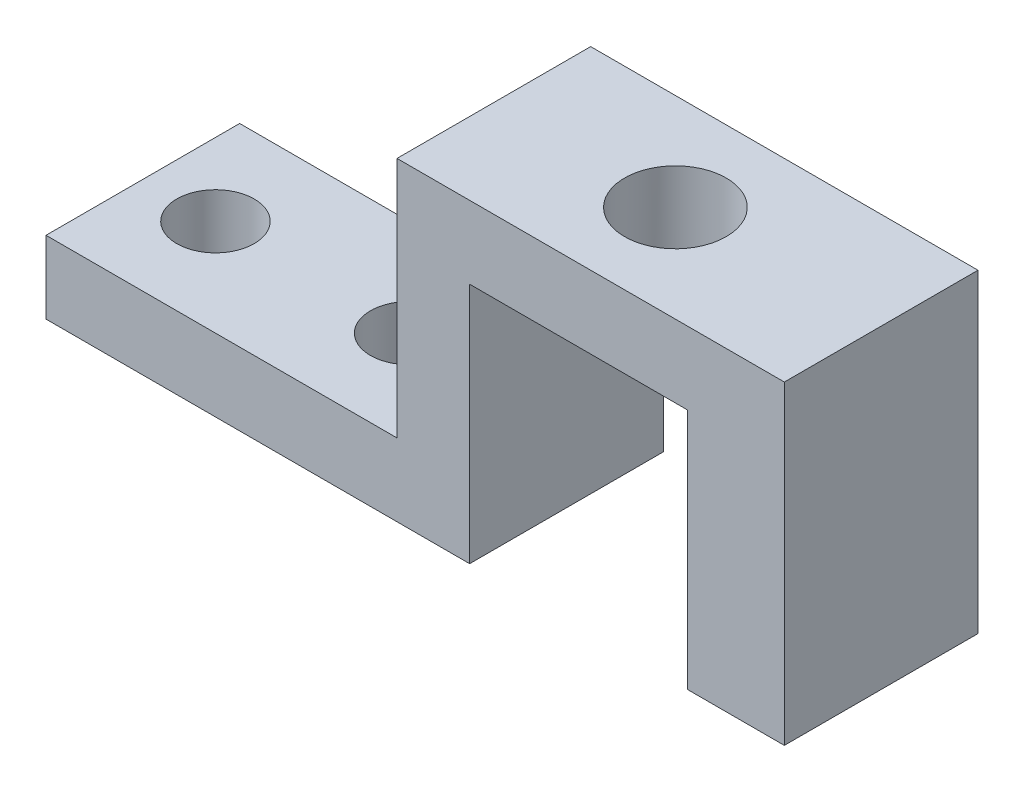
SolidWorks part; units mm, degrees
ref_plane "前视基准面" through (0, 0, 0) normal (0, 0, 1) x (1, 0, 0)
ref_plane "上视基准面" through (0, 0, 0) normal (0, 1, 0) x (1, 0, 0)
ref_plane "右视基准面" through (0, 0, 0) normal (1, 0, 0) x (0, 0, -1)
sketch "草图1" plane through (0, 0, 0) normal (0, 0, 1) x (1, 0, 0)
  line L0 (0, 0) -> (0, 3)
  line L1 (0, 3) -> (14.5, 3)
  line L2 (14.5, 3) -> (14.5, 13)
  line L3 (14.5, 13) -> (30.5, 13)
  line L4 (30.5, 13) -> (30.5, 0)
  line L7 (30.5, 0) -> (26.5, 0)
  line L8 (26.5, 0) -> (26.5, 10)
  line L9 (26.5, 10) -> (17.5, 10)
  line L10 (17.5, 10) -> (17.5, 0)
  line L11 (17.5, 0) -> (0, 0)
  point P16 (22, 10)
  dimension "D1" = 3
  dimension "D2" = 3
  dimension "D3" = 4
  dimension "D4" = 22
  dimension "D5" = 3
  dimension "D6" = 9
  dimension "D7" = 13
extrude "凸台-拉伸1" add sketch "草图1" along normal blind 8
sketch "草图2" plane through (0, 10, 0) normal (0, -1, 0) x (1, 0, 0)
  line L0 (0, 4) -> (30.5, 4) construction
  line L1 (0, 8) -> (0, 0) construction
  line L2 (30.5, 8) -> (30.5, 0) construction
  line L3 (22, 8) -> (22, 0) construction
  line L4 (17.5, 8) -> (26.5, 8) construction
  line L5 (17.5, 0) -> (26.5, 0) construction
  circle A0 centre (3, 4) radius 1.6
  circle A1 centre (11, 4) radius 1.6
  circle A2 centre (22, 4) radius 2.1
  dimension "D1" = 4.2
  dimension "D2" = 11
  dimension "D3" = 8
  dimension "D4" = 3.2
extrude "切除-拉伸1" cut sketch "草图2" against normal through all both and the other way through all
